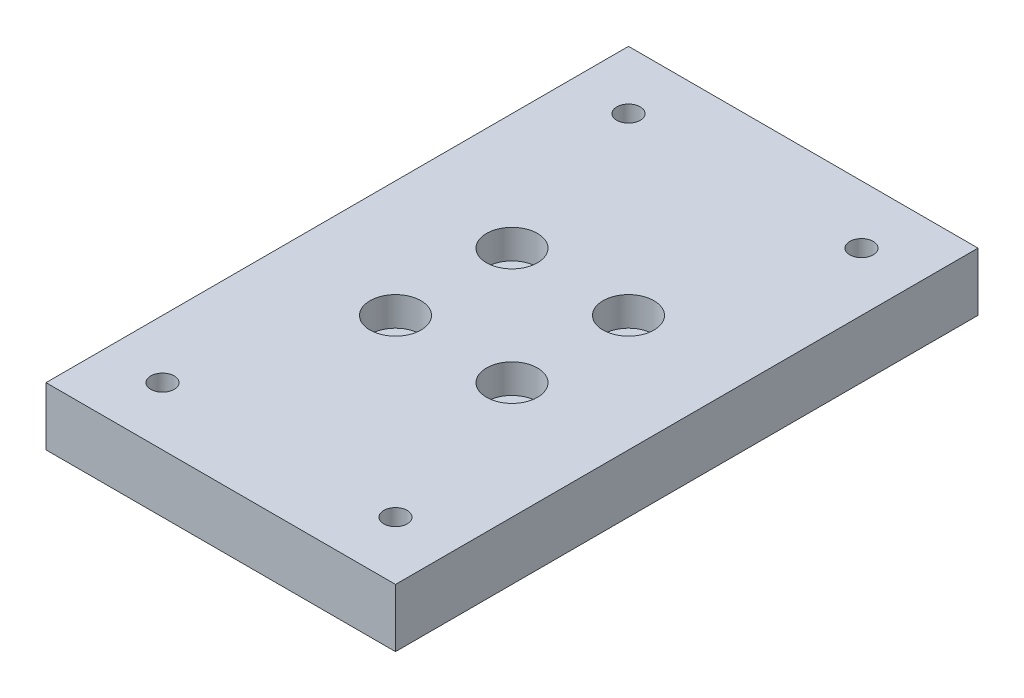
SolidWorks part; units mm, degrees
ref_plane "Front Plane" through (0, 0, 0) normal (0, 0, 1) x (1, 0, 0)
ref_plane "Top Plane" through (0, 0, 0) normal (0, 1, 0) x (1, 0, 0)
ref_plane "Right Plane" through (0, 0, 0) normal (1, 0, 0) x (0, 0, -1)
sketch "Sketch1" plane through (0, 0, 0) normal (0, 1, 0) x (1, 0, 0)
  line L1 (-38.1, -63.5) -> (38.1, -63.5)
  line L2 (-38.1, -63.5) -> (-38.1, 63.5)
  line L3 (-38.1, 63.5) -> (38.1, 63.5)
  line L4 (38.1, -63.5) -> (38.1, 63.5)
  line L5 (-38.1, -63.5) -> (38.1, 63.5) construction
  line L6 (-38.1, 63.5) -> (38.1, -63.5) construction
  circle A0 centre (-12.7, 12.7) radius 3.429
  circle A1 centre (12.7, 12.7) radius 3.429
  circle A4 centre (12.7, -12.7) radius 3.429
  circle A13 centre (-12.7, -12.7) radius 3.429
  point P0 (0, 0)
  dimension "D1" = 6.858
  dimension "D2" = 12.7
  dimension "D3" = 127
  dimension "D4" = 76.2
  dimension "D5" = 12.7
  dimension "D6" = 2
  dimension "D7" = 2
extrude "Boss-Extrude1" add sketch "Sketch1" along normal blind 12.7
hole_wizard "CBORE for 1/4 Socket Head Cap Screw1" positions "Sketch2" profile "Sketch3" counterbore size "1/4" standard "ANSI Inch" end condition through all
sketch "Sketch2" plane through (0, 12.7, 0) normal (0, 1, 0) x (1, 0, 0)
  point P0 (-12.7, 12.7)
  point P3 (12.7, 12.7)
  point P6 (12.7, -12.7)
  point P9 (-12.7, -12.7)
  point P12 (-108.2268, 58.2593)
sketch "Sketch3" plane through (-12.7, 12.7, -12.7) normal (1, 0, 0) x (0, 0, 1)
  line L0 (0, 0) -> (0, 12.7)
  line L1 (0, 12.7) -> (3.3782, 12.7)
  line L3 (3.3782, 12.7) -> (3.3782, 6.35)
  line L4 (3.3782, 6.35) -> (5.5562, 6.35)
  line L5 (5.5562, 6.35) -> (5.5563, 0)
  line L7 (5.5563, 0) -> (0, 0)
  line L11 (0, -6.35) -> (0, 107.95) construction
  dimension "Thru Hole Dia." = 6.7564
  dimension "Thru Hole Depth" = 12.7
  dimension "C'Bore Dia." = 11.1125
  dimension "C'Bore Depth" = 6.35
hole_wizard "1/4-20 Tapped Hole1" positions "Sketch4" profile "Sketch5" tap size "1/4-20" standard "ANSI Inch" end condition through all
sketch "Sketch4" plane through (0, 12.7, 0) normal (0, 1, 0) x (1, 0, 0)
  point P0 (25.4, 50.8)
  point P2 (-25.4, 50.8)
  point P4 (-25.4, -50.8)
  point P6 (25.4, -50.8)
  dimension "D1" = 25.4
  dimension "D2" = 50.8
  dimension "D3" = 50.8
  dimension "D4" = 101.6
sketch "Sketch5" plane through (25.4, 12.7, -50.8) normal (1, 0, 0) x (0, 0, 1)
  line L0 (0, 0) -> (0, 12.7)
  line L1 (0, 12.7) -> (2.5527, 12.7)
  line L2 (2.5527, 12.7) -> (2.5527, 0)
  line L5 (2.5527, 0) -> (0, 0)
  line L11 (0, -6.35) -> (0, 107.95) construction
  dimension "Thru Tap Drill Dia." = 5.1054
  dimension "Thru Tap Drill Depth" = 12.7
cosmetic thread "Hole Thread1" parameters "D2"=6.35
cosmetic thread "Hole Thread2" parameters "D2"=6.35
cosmetic thread "Hole Thread3" parameters "D2"=6.35
cosmetic thread "Hole Thread4" parameters "D2"=6.35
